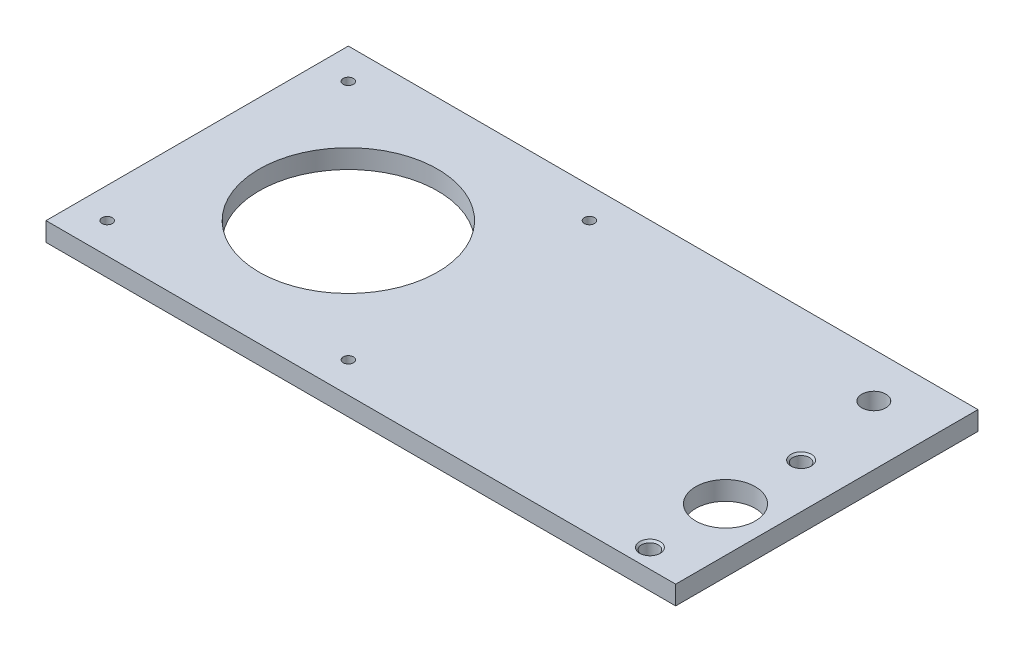
SolidWorks part; units mm, degrees
material "6061 Alloy"
ref_plane "Plan de face" through (0, 0, 0) normal (0, 0, 1) x (1, 0, 0)
ref_plane "Plan de dessus" through (0, 0, 0) normal (0, 1, 0) x (1, 0, 0)
ref_plane "Plan de droite" through (0, 0, 0) normal (1, 0, 0) x (0, 0, -1)
sketch "Sketch1" plane through (0, 0, 0) normal (0, 1, 0) x (1, 0, 0)
  line L1 (-50.8, 50.8) -> (50.8, 50.8)
  line L2 (-50.8, 50.8) -> (-50.8, -50.8)
  line L3 (-50.8, -50.8) -> (50.8, -50.8)
  line L4 (50.8, 50.8) -> (50.8, -50.8)
  line L5 (-50.8, 50.8) -> (50.8, -50.8) construction
  line L6 (-50.8, -50.8) -> (50.8, 50.8) construction
  line L7 (-40.513, -40.513) -> (40.513, -40.513) construction
  line L8 (-40.513, -40.513) -> (-40.513, 40.513) construction
  line L9 (-40.513, 40.513) -> (40.513, 40.513) construction
  line L10 (40.513, -40.513) -> (40.513, 40.513) construction
  line L11 (-40.513, -40.513) -> (40.513, 40.513) construction
  line L12 (-40.513, 40.513) -> (40.513, -40.513) construction
  line L20 (-50.8, 50.8) -> (-50.8, -50.8)
  line L24 (50.8, 50.8) -> (160.8, 50.8)
  line L25 (50.8, 50.8) -> (50.8, -50.8)
  line L26 (50.8, -50.8) -> (160.8, -50.8)
  line L27 (160.8, 50.8) -> (160.8, -50.8)
  line L28 (145.8, 6.35) -> (145.8, -44.45) construction
  circle A0 centre (0, 0) radius 30
  circle A1 centre (-40.513, 40.513) radius 2.1 construction
  circle A3 centre (40.513, 40.513) radius 2.1 construction
  circle A6 centre (40.513, -40.513) radius 2.1 construction
  circle A8 centre (-40.513, -40.513) radius 2.1 construction
  circle A11 centre (145.8, -19.05) radius 31.75 construction
  circle A12 centre (145.8, -19.05) radius 25.4 construction
  circle A13 centre (140.8, 35.8) radius 4.025
  circle A14 centre (145.8, -19.05) radius 10
  circle A15 centre (145.8, 6.35) radius 2.1 construction
  circle A17 centre (145.8, -44.45) radius 2.1 construction
  circle A19 centre (0, 0) radius 81.5 construction
  circle A20 centre (140.8, 35.8) radius 41 construction
  point P0 (0, 0)
  dimension "D2" = 60
  dimension "D7" = 4.2
  dimension "D10" = 4.2
  dimension "D11" = 4.2
  dimension "D13" = 4.2
  dimension "D22" = 63.5
  dimension "D23" = 50.8
  dimension "D27" = 20
  dimension "D28" = 4.2
  dimension "D30" = 4.2
  dimension "D24" = 8.05
  dimension "D4" = 163
  dimension "D8" = 82
  dimension "D5" = 81.026
  dimension "D6" = 81.026
  dimension "D21" = 110
  dimension "D25" = 15
  dimension "D26" = 20
  dimension "D15" = 101.6
  dimension "D9" = 15
extrude "Boss-Extrude1" add sketch "Sketch1" along normal blind 6.35
hole_wizard "#8-32 Tapped Hole1" positions "Sketch2" profile "Sketch3" tap size "#8-32" standard "ANSI Inch" end condition up to next
sketch "Sketch2" plane through (0, 6.35, 0) normal (0, 1, 0) x (1, 0, 0)
  point P2 (-40.513, 40.513)
  point P5 (40.513, 40.513)
  point P8 (40.513, -40.513)
  point P11 (-40.513, -40.513)
sketch "Sketch3" plane through (-40.513, 6.35, -40.513) normal (1, 0, 0) x (0, 0, 1)
  line L0 (0, 0) -> (0, 6.35)
  line L1 (0, 6.35) -> (1.7272, 6.35)
  line L2 (1.7272, 6.35) -> (1.7272, 0)
  line L5 (1.7272, 0) -> (0, 0)
  line L11 (0, -6.35) -> (0, 107.95) construction
  dimension "Thru Tap Drill Dia." = 3.4544
  dimension "Thru Tap Drill Depth" = 6.35
cosmetic thread "Hole Thread1" parameters "D2"=4.1656
cosmetic thread "Hole Thread2" parameters "D2"=4.1656
cosmetic thread "Hole Thread3" parameters "D2"=4.1656
cosmetic thread "Hole Thread4" parameters "D2"=4.1656
hole_wizard "#10 Clearance Hole1" positions "Sketch4" profile "Sketch5" hole size "#10" standard "ANSI Inch" end condition up to next
sketch "Sketch4" plane through (0, 6.35, 0) normal (0, 1, 0) x (1, 0, 0)
  point P0 (145.8, 6.35)
  point P3 (145.8, -44.45)
sketch "Sketch5" plane through (145.8, 6.35, -6.35) normal (1, 0, 0) x (0, 0, 1)
  line L0 (0, 0) -> (0, 6.35)
  line L1 (0, 6.35) -> (2.8067, 6.35)
  line L2 (2.8067, 6.35) -> (2.8067, 0.635)
  line L3 (2.8067, 0.635) -> (3.4417, 0)
  line L5 (3.4417, 0) -> (0, 0)
  line L6 (-2.8067, 0.635) -> (-3.4417, 0) construction
  line L11 (0, -6.35) -> (0, 107.95) construction
  dimension "Thru Hole Dia." = 5.6134
  dimension "Thru Hole Depth" = 6.35
  dimension "Near C'Sink Dia." = 6.8834
  dimension "Near C'Sink Angle" = 90
equation "\"D5@Sketch1\"=3.19in"
equation "\"D6@Sketch1\"=3.19in"
equation "\"D10@Sketch1\"=\"D7@Sketch1\""
equation "\"D11@Sketch1\"=\"D7@Sketch1\""
equation "\"D13@Sketch1\"=\"D7@Sketch1\""
